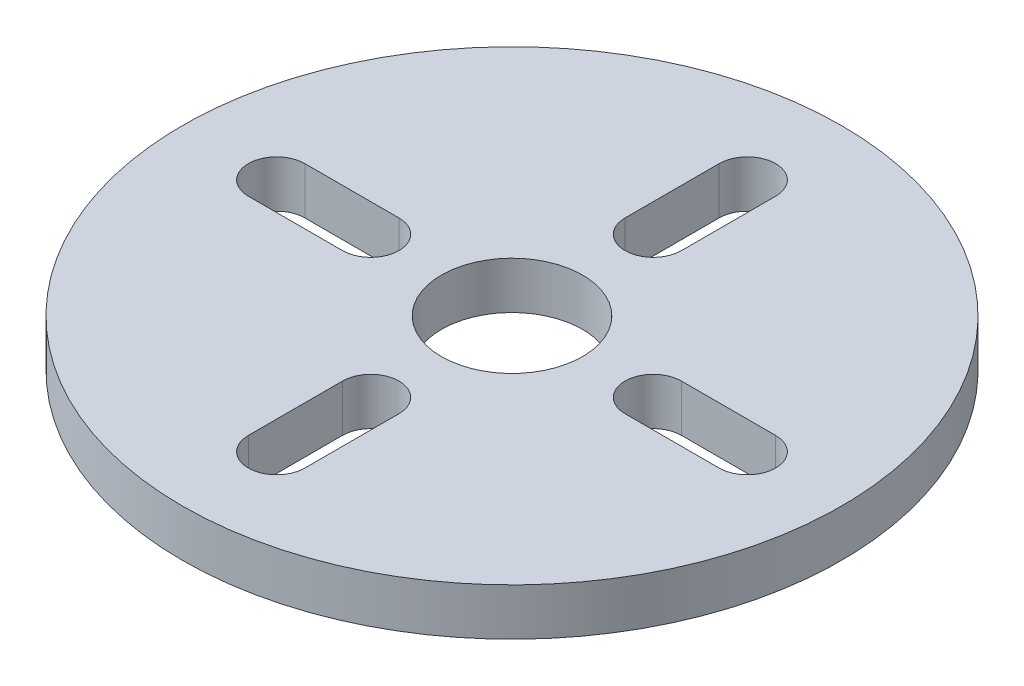
SolidWorks part; units mm, degrees
ref_plane "Front Plane" through (0, 0, 0) normal (0, 0, 1) x (1, 0, 0)
ref_plane "Top Plane" through (0, 0, 0) normal (0, 1, 0) x (1, 0, 0)
ref_plane "Right Plane" through (0, 0, 0) normal (1, 0, 0) x (0, 0, -1)
sketch "Sketch1" plane through (0, 0, 0) normal (0, 1, 0) x (1, 0, 0)
  circle A0 centre (0, 0) radius 14
  dimension "D1" = 28
extrude "Boss-Extrude1" add sketch "Sketch1" along normal blind 2
sketch "Sketch2" plane through (0, 2, 0) normal (0, 1, 0) x (1, 0, 0)
  line L0 (0, 0) -> (0, -50000) construction
  line L1 (0, 0) -> (-50000, 0) construction
  line L2 (0, 10) -> (0, 6) construction
  line L3 (1.2, 10) -> (1.2, 6)
  line L4 (-1.2, 10) -> (-1.2, 6)
  line L5 (10, 0) -> (6, 0) construction
  line L6 (10, -1.2) -> (6, -1.2)
  line L7 (10, 1.2) -> (6, 1.2)
  line L8 (0, -10) -> (0, -6) construction
  line L9 (-1.2, -10) -> (-1.2, -6)
  line L10 (1.2, -10) -> (1.2, -6)
  line L11 (-10, 0) -> (-6, 0) construction
  line L12 (-10, 1.2) -> (-6, 1.2)
  line L13 (-10, -1.2) -> (-6, -1.2)
  arc A0 (1.2, 10) -> (-1.2, 10) centre (0, 10) ccw
  arc A1 (-1.2, 6) -> (1.2, 6) centre (0, 6) ccw
  arc A2 (10, -1.2) -> (10, 1.2) centre (10, 0) ccw
  arc A3 (6, 1.2) -> (6, -1.2) centre (6, 0) ccw
  arc A4 (-1.2, -10) -> (1.2, -10) centre (0, -10) ccw
  arc A5 (1.2, -6) -> (-1.2, -6) centre (0, -6) ccw
  arc A6 (-10, 1.2) -> (-10, -1.2) centre (-10, 0) ccw
  arc A7 (-6, -1.2) -> (-6, 1.2) centre (-6, 0) ccw
  circle A8 centre (0, 0) radius 3
  point P7 (0, 8)
  point P17 (8, 0)
  point P24 (0, -8)
  point P31 (-8, 0)
  point P36 (0, 0)
  dimension "D4" = 6
  dimension "D1" = 8
  dimension "D2" = 4
  dimension "D3" = 2.4
extrude "Cut-Extrude1" cut sketch "Sketch2" against normal through all
